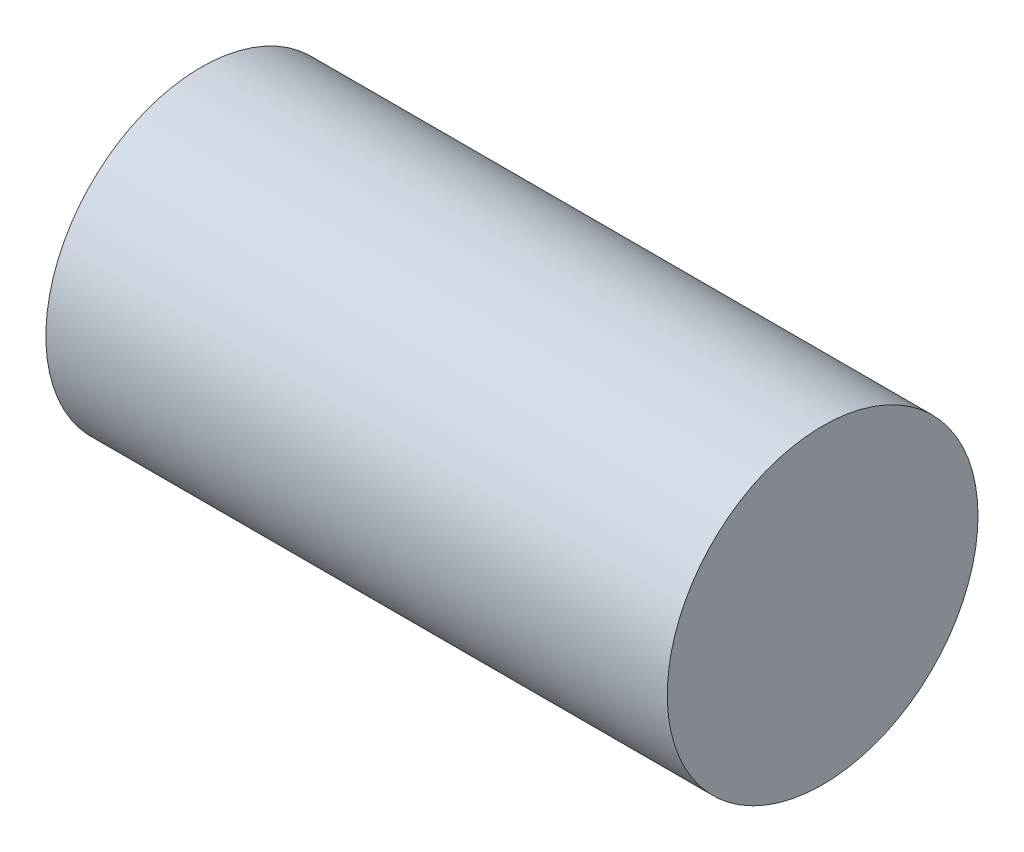
SolidWorks part; units mm, degrees
ref_plane "Plan de face" through (0, 0, 0) normal (0, 0, 1) x (1, 0, 0)
ref_plane "Plan de dessus" through (0, 0, 0) normal (0, 1, 0) x (1, 0, 0)
ref_plane "Plan de droite" through (0, 0, 0) normal (1, 0, 0) x (0, 0, -1)
sketch "Esquisse1" plane through (0, 0, 0) normal (1, 0, 0) x (0, 0, -1)
  circle A0 centre (0, 0) radius 1
  dimension "D1" = 2
extrude "Boss.-Extru.1" add sketch "Esquisse1" along normal blind 4
